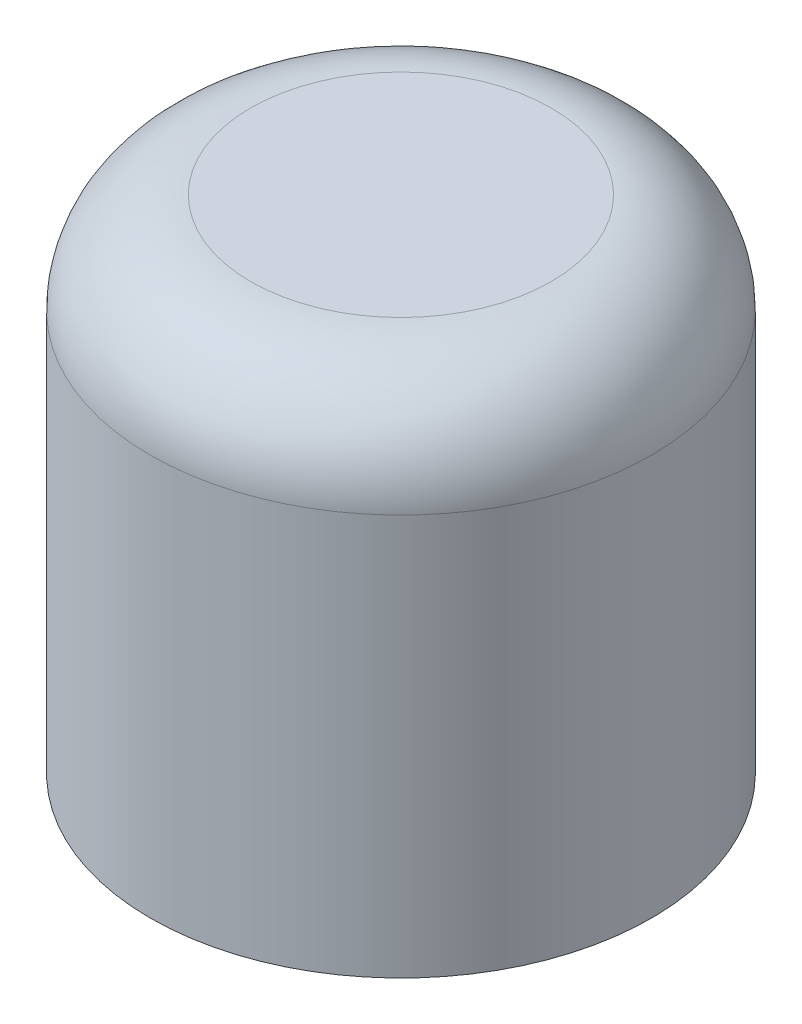
SolidWorks part; units mm, degrees
ref_plane "Front" through (0, 0, 0) normal (0, 0, 1) x (1, 0, 0)
ref_plane "Top" through (0, 0, 0) normal (0, 1, 0) x (1, 0, 0)
ref_plane "Right" through (0, 0, 0) normal (1, 0, 0) x (0, 0, -1)
sketch "Sketch1" plane through (0, 0, 0) normal (0, 1, 0) x (1, 0, 0)
  circle A0 centre (0, 0) radius 50
  dimension "D1" = 100
extrude "Boss-Extrude1" add sketch "Sketch1" along normal blind 100
fillet "Fillet1" radius 20 1 edges at (0, 100, 50)
sketch "Sketch4" plane through (0, 0, 0) normal (0, -1, 0) x (1, 0, 0)
  circle A0 centre (0, 0) radius 45
  dimension "D1" = 90
extrude "Cut-Extrude1" cut sketch "Sketch4" against normal blind 80
